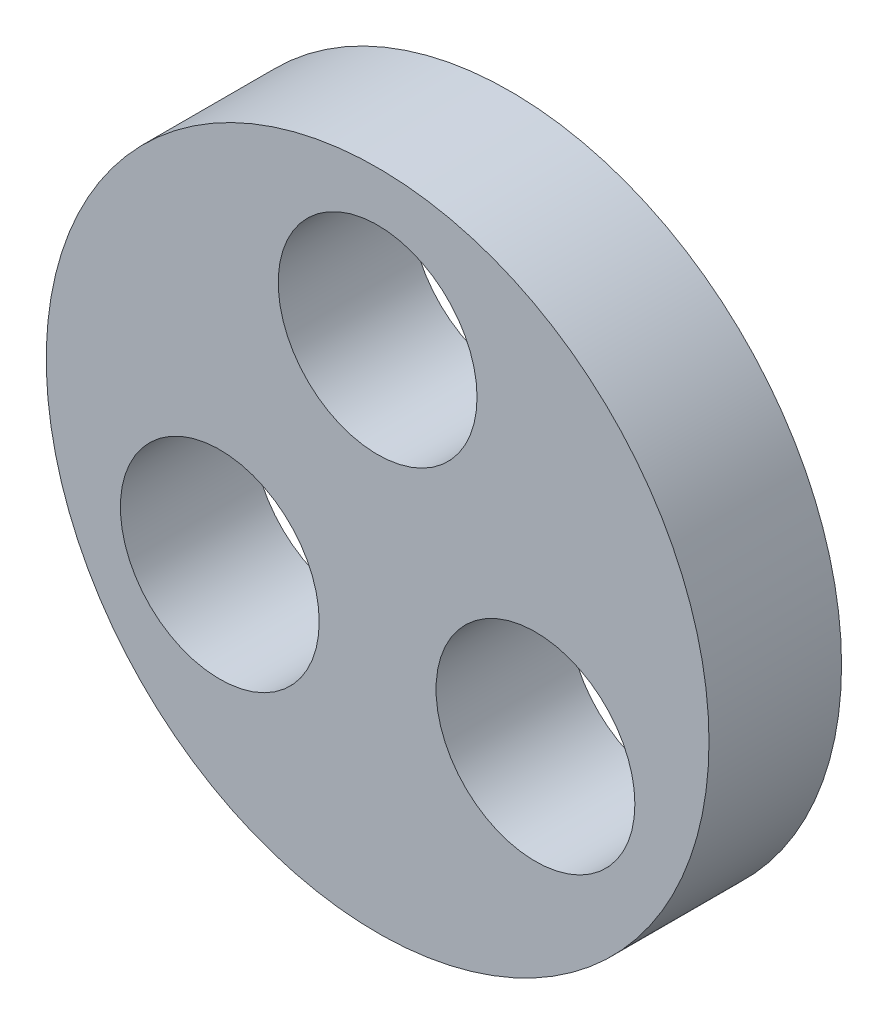
SolidWorks part; units mm, degrees
ref_plane "Front Plane" through (0, 0, 0) normal (0, 0, 1) x (1, 0, 0)
ref_plane "Top Plane" through (0, 0, 0) normal (0, 1, 0) x (1, 0, 0)
ref_plane "Right Plane" through (0, 0, 0) normal (1, 0, 0) x (0, 0, -1)
sketch "Sketch1" plane through (0, 0, 0) normal (0, 0, 1) x (1, 0, 0)
  circle A0 centre (0, 0) radius 7.9375
  circle A1 centre (0, 4.3656) radius 2.3813
  circle A2 centre (3.7807, -2.1828) radius 2.3813
  circle A3 centre (-3.7807, -2.1828) radius 2.3813
  point P11 (0, 0)
  dimension "D1" = 15.875
  dimension "D2" = 4.7625
  dimension "D3" = 4.3656
  dimension "D4" = 3
extrude "Boss-Extrude1" add sketch "Sketch1" along normal blind 3.175
